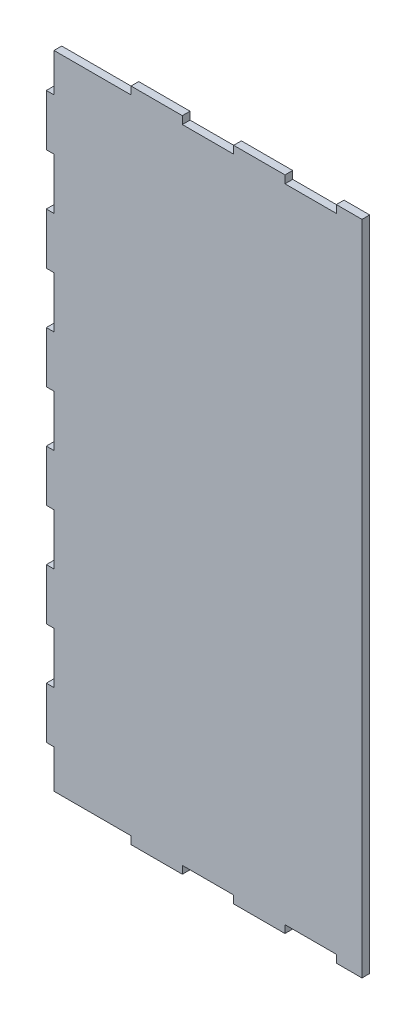
SolidWorks part; units mm, degrees
ref_plane "Front Plane" through (0, 0, 0) normal (0, 0, 1) x (1, 0, 0)
ref_plane "Top Plane" through (0, 0, 0) normal (0, 1, 0) x (1, 0, 0)
ref_plane "Right Plane" through (0, 0, 0) normal (1, 0, 0) x (0, 0, -1)
sketch "Эскиз2" plane through (0, 0, 0) normal (0, 0, 1) x (1, 0, 0)
  line L0 (252.1992, 250.1414) -> (259.9123, 250.1414)
  line L1 (259.9123, 250.1414) -> (259.9123, 254.5354)
  line L2 (259.9123, 254.5354) -> (283.6064, 254.5354)
  line L3 (283.6064, 254.5354) -> (283.6064, 250.1414)
  line L4 (283.6064, 250.1414) -> (305.7717, 250.1414)
  line L5 (305.7717, 250.1414) -> (305.7717, 254.5354)
  line L6 (305.7717, 254.5354) -> (329.4658, 254.5354)
  line L7 (329.4658, 254.5354) -> (329.4658, 250.1414)
  line L8 (329.4658, 250.1414) -> (360.0387, 250.1414)
  line L9 (360.0387, 250.1414) -> (360.0387, 226.7063)
  line L10 (360.0387, 226.7063) -> (365.7711, 226.7063)
  line L11 (365.7711, 226.7063) -> (365.7711, 208.5441)
  line L12 (365.7711, 208.5441) -> (360.0387, 208.5441)
  line L13 (360.0387, 208.5441) -> (360.0387, 191.5536)
  line L14 (360.0387, 191.5536) -> (365.7711, 191.5536)
  line L15 (365.7711, 191.5536) -> (365.7711, 173.3914)
  line L16 (365.7711, 173.3914) -> (360.0387, 173.3914)
  line L17 (360.0387, 173.3914) -> (360.0387, 156.401)
  line L18 (360.0387, 156.401) -> (365.7711, 156.401)
  line L19 (365.7711, 156.401) -> (365.7711, 138.2388)
  line L20 (365.7711, 138.2388) -> (360.0387, 138.2388)
  line L21 (360.0387, 138.2388) -> (360.0387, 121.2484)
  line L22 (360.0387, 121.2484) -> (365.7711, 121.2484)
  line L23 (365.7711, 121.2484) -> (365.7711, 103.0862)
  line L24 (365.7711, 103.0862) -> (360.0387, 103.0862)
  line L25 (360.0387, 103.0862) -> (360.0387, 86.0957)
  line L26 (360.0387, 86.0957) -> (365.7711, 86.0957)
  line L27 (365.7711, 86.0957) -> (365.7711, 67.9335)
  line L28 (365.7711, 67.9335) -> (360.0387, 67.9335)
  line L29 (360.0387, 67.9335) -> (360.0387, 50.9431)
  line L30 (360.0387, 50.9431) -> (365.7711, 50.9431)
  line L31 (365.7711, 50.9431) -> (365.7711, 32.7809)
  line L32 (365.7711, 32.7809) -> (360.0387, 32.7809)
  line L33 (360.0387, 0.0593) -> (328.8776, 0.0593)
  line L34 (328.8776, 0.0593) -> (328.8776, -4.3348)
  line L35 (328.8776, -4.3348) -> (305.1835, -4.3348)
  line L36 (305.1835, -4.3348) -> (305.1835, 0.0593)
  line L37 (305.1835, 0.0593) -> (283.0182, 0.0593)
  line L38 (283.0182, 0.0593) -> (283.0182, -4.3348)
  line L39 (283.0182, -4.3348) -> (259.3241, -4.3348)
  line L40 (259.3241, -4.3348) -> (259.3241, 0.0593)
  line L41 (259.3241, 0.0593) -> (251.611, 0.0593)
  line L42 (251.611, 0.0593) -> (237.1588, 0.0593)
  line L43 (237.1588, 0.0593) -> (237.1588, -4.3348)
  line L44 (237.1588, -4.3348) -> (213.4647, -4.3348)
  line L45 (213.4647, -4.3348) -> (213.4647, 0.0593)
  line L46 (213.4647, 0.0593) -> (191.2994, 0.0593)
  line L47 (191.2994, 0.0593) -> (191.2994, -4.3348)
  line L48 (191.2994, -4.3348) -> (167.6053, -4.3348)
  line L49 (167.6053, -4.3348) -> (167.6053, 0.0593)
  line L50 (167.6053, 0.0593) -> (145.4399, 0.0593)
  line L51 (145.4399, 0.0593) -> (145.4399, -4.3348)
  line L52 (145.4399, -4.3348) -> (121.7459, -4.3348)
  line L53 (121.7459, -4.3348) -> (121.7459, 0.0593)
  line L54 (121.7459, 0.0593) -> (99.5805, 0.0593)
  line L55 (99.5805, 0.0593) -> (99.5805, -4.3348)
  line L56 (99.5805, -4.3348) -> (75.8865, -4.3348)
  line L57 (75.8865, -4.3348) -> (75.8865, 0.0593)
  line L58 (75.8865, 0.0593) -> (53.7211, 0.0593)
  line L59 (53.7211, 0.0593) -> (53.7211, -4.3348)
  line L60 (53.7211, -4.3348) -> (30.0271, -4.3348)
  line L61 (30.0271, -4.3348) -> (30.0271, 0.0593)
  line L62 (30.0271, 0.0593) -> (0.0424, 0.0593)
  line L63 (0.0424, 0.0593) -> (0.0424, 32.7809)
  line L64 (0.0424, 32.7809) -> (-5.6901, 32.7809)
  line L65 (-5.6901, 32.7809) -> (-5.6901, 50.9431)
  line L66 (-5.6901, 50.9431) -> (0.0424, 50.9431)
  line L67 (0.0424, 50.9431) -> (0.0424, 67.9335)
  line L68 (0.0424, 67.9335) -> (-5.6901, 67.9335)
  line L69 (-5.6901, 67.9335) -> (-5.6901, 86.0957)
  line L70 (-5.6901, 86.0957) -> (0.0424, 86.0957)
  line L71 (0.0424, 86.0957) -> (0.0424, 103.0862)
  line L72 (0.0424, 103.0862) -> (-5.6901, 103.0862)
  line L73 (-5.6901, 103.0862) -> (-5.6901, 121.2484)
  line L74 (-5.6901, 121.2484) -> (0.0424, 121.2484)
  line L75 (0.0424, 121.2484) -> (0.0424, 138.2388)
  line L76 (0.0424, 138.2388) -> (-5.6901, 138.2388)
  line L77 (-5.6901, 138.2388) -> (-5.6901, 156.401)
  line L78 (-5.6901, 156.401) -> (0.0424, 156.401)
  line L79 (0.0424, 156.401) -> (0.0424, 173.3914)
  line L80 (0.0424, 173.3914) -> (-5.6901, 173.3914)
  line L81 (-5.6901, 173.3914) -> (-5.6901, 191.5536)
  line L82 (-5.6901, 191.5536) -> (0.0424, 191.5536)
  line L83 (0.0424, 191.5536) -> (0.0424, 208.5441)
  line L84 (0.0424, 208.5441) -> (-5.6901, 208.5441)
  line L85 (-5.6901, 208.5441) -> (-5.6901, 226.7063)
  line L86 (-5.6901, 226.7063) -> (0.0424, 226.7063)
  line L87 (0.0424, 226.7063) -> (0.0424, 250.1414)
  line L88 (0.0424, 250.1414) -> (30.6153, 250.1414)
  line L89 (30.6153, 250.1414) -> (30.6153, 254.5354)
  line L90 (30.6153, 254.5354) -> (54.3093, 254.5354)
  line L91 (54.3093, 254.5354) -> (54.3093, 250.1414)
  line L92 (54.3093, 250.1414) -> (76.4747, 250.1414)
  line L93 (76.4747, 250.1414) -> (76.4747, 254.5354)
  line L94 (76.4747, 254.5354) -> (100.1687, 254.5354)
  line L95 (100.1687, 254.5354) -> (100.1687, 250.1414)
  line L96 (100.1687, 250.1414) -> (122.3341, 250.1414)
  line L97 (122.3341, 250.1414) -> (122.3341, 254.5354)
  line L98 (122.3341, 254.5354) -> (146.0281, 254.5354)
  line L99 (146.0281, 254.5354) -> (146.0281, 250.1414)
  line L100 (146.0281, 250.1414) -> (168.1935, 250.1414)
  line L101 (168.1935, 250.1414) -> (168.1935, 254.5354)
  line L102 (168.1935, 254.5354) -> (191.8876, 254.5354)
  line L103 (191.8876, 254.5354) -> (191.8876, 250.1414)
  line L104 (191.8876, 250.1414) -> (214.0529, 250.1414)
  line L105 (214.0529, 250.1414) -> (214.0529, 254.5354)
  line L106 (214.0529, 254.5354) -> (237.747, 254.5354)
  line L107 (237.747, 254.5354) -> (237.747, 250.1414)
  line L108 (237.747, 250.1414) -> (252.1992, 250.1414)
  line L109 (-2.9475, -11.1911) -> (27.4972, -11.1911)
  line L110 (27.4972, -11.1911) -> (27.4972, -15.5023)
  line L111 (27.4972, -15.5023) -> (51.9003, -15.5023)
  line L112 (51.9003, -15.5023) -> (51.9003, -11.1911)
  line L113 (51.9003, -11.1911) -> (73.3564, -11.1911)
  line L114 (73.3564, -11.1911) -> (73.3564, -15.5023)
  line L115 (73.3564, -15.5023) -> (97.7419, -15.5023)
  line L116 (97.7419, -15.5023) -> (97.7419, -11.1911)
  line L117 (97.7419, -11.1911) -> (119.1409, -11.1911)
  line L118 (119.1409, -11.1911) -> (119.1409, -15.5023)
  line L119 (119.1409, -15.5023) -> (143.6357, -15.5023)
  line L120 (143.6357, -15.5023) -> (143.6357, -11.1911)
  line L121 (143.6357, -11.1911) -> (165.0694, -11.1911)
  line L122 (165.0694, -11.1911) -> (165.0694, -15.5023)
  line L123 (165.0694, -15.5023) -> (189.4359, -15.5023)
  line L124 (189.4359, -15.5023) -> (189.4359, -11.1911)
  line L125 (189.4359, -11.1911) -> (210.8089, -11.1911)
  line L126 (210.8089, -11.1911) -> (210.8089, -15.5023)
  line L127 (210.8089, -15.5023) -> (235.3017, -15.5023)
  line L128 (235.3017, -15.5023) -> (235.3017, -11.1911)
  line L129 (235.3017, -11.1911) -> (256.7496, -11.1911)
  line L130 (256.7496, -11.1911) -> (256.7496, -15.5023)
  line L131 (256.7496, -15.5023) -> (281.117, -15.5023)
  line L132 (281.117, -15.5023) -> (281.117, -11.1911)
  line L133 (281.117, -11.1911) -> (302.5894, -11.1911)
  line L134 (302.5894, -11.1911) -> (302.5894, -15.5023)
  line L135 (302.5894, -15.5023) -> (327.148, -15.5023)
  line L136 (327.148, -15.5023) -> (327.148, -11.1911)
  line L137 (327.148, -11.1911) -> (357.4727, -11.1911)
  line L138 (357.4727, -11.1911) -> (357.4727, -22.8779)
  line L139 (357.4727, -22.8779) -> (365.5155, -22.8779)
  line L140 (365.5155, -22.8779) -> (365.509, -29.7472)
  line L141 (365.509, -29.7472) -> (357.4727, -29.7472)
  line L142 (357.4727, -29.7472) -> (357.4727, -42.673)
  line L143 (357.4727, -42.673) -> (327.148, -42.673)
  line L144 (327.148, -42.673) -> (327.148, -38.9463)
  line L145 (327.148, -38.9463) -> (302.5894, -38.9463)
  line L146 (302.5894, -38.9463) -> (302.5894, -42.673)
  line L147 (302.5894, -42.673) -> (281.117, -42.673)
  line L148 (281.117, -42.673) -> (281.117, -38.9463)
  line L149 (281.117, -38.9463) -> (256.7496, -38.9463)
  line L150 (256.7496, -38.9463) -> (256.7496, -42.673)
  line L151 (256.7496, -42.673) -> (235.3017, -42.673)
  line L152 (235.3017, -42.673) -> (235.3017, -38.9463)
  line L153 (235.3017, -38.9463) -> (210.8089, -38.9463)
  line L154 (210.8089, -38.9463) -> (210.8089, -42.673)
  line L155 (210.8089, -42.673) -> (189.4359, -42.673)
  line L156 (189.4359, -42.673) -> (189.4353, -38.9463)
  line L157 (189.4353, -38.9463) -> (165.0694, -38.9463)
  line L158 (165.0694, -38.9463) -> (165.0694, -42.673)
  line L159 (165.0694, -42.673) -> (143.6357, -42.673)
  line L160 (143.6357, -42.673) -> (143.6357, -38.9463)
  line L161 (143.6357, -38.9463) -> (119.1409, -38.9463)
  line L162 (119.1409, -38.9463) -> (119.1409, -42.673)
  line L163 (119.1409, -42.673) -> (97.7419, -42.673)
  line L164 (97.7419, -42.673) -> (97.7419, -38.9463)
  line L165 (97.7419, -38.9463) -> (73.3564, -38.9463)
  line L166 (73.3564, -38.9463) -> (73.3564, -42.673)
  line L167 (73.3564, -42.673) -> (51.9003, -42.673)
  line L168 (51.9003, -42.673) -> (51.9003, -38.9463)
  line L169 (51.9003, -38.9463) -> (27.4972, -38.9463)
  line L170 (27.4972, -38.9463) -> (27.4972, -42.673)
  line L171 (27.4972, -42.673) -> (-2.9475, -42.673)
  line L172 (-2.9475, -42.673) -> (-2.9475, -29.9471)
  line L173 (-2.9475, -29.9471) -> (-9.6507, -29.9471)
  line L174 (-9.6507, -29.9471) -> (-9.6507, -23.0778)
  line L175 (-9.6507, -23.0778) -> (-2.9475, -23.0778)
  line L176 (-2.9475, -23.0778) -> (-2.9475, -11.1911)
  line L177 (60.6272, -30.2931) -> (60.6272, -23.0367)
  line L178 (60.6272, -23.0367) -> (63.4658, -23.0367)
  line L179 (63.4658, -23.0367) -> (63.4658, -30.2931)
  line L180 (63.4658, -30.2931) -> (60.6272, -30.2931)
  line L181 (30.6174, -30.2532) -> (30.6174, -23.0192)
  line L182 (30.6174, -23.0192) -> (33.456, -23.0192)
  line L183 (33.456, -23.0192) -> (33.456, -30.2532)
  line L184 (33.456, -30.2532) -> (30.6174, -30.2532)
  line L185 (90.633, -30.2432) -> (90.633, -23.0092)
  line L186 (90.633, -23.0092) -> (93.4716, -23.0092)
  line L187 (93.4716, -23.0092) -> (93.4716, -30.2432)
  line L188 (93.4716, -30.2432) -> (90.633, -30.2432)
  line L189 (120.6308, -30.2393) -> (120.6308, -23.0267)
  line L190 (120.6308, -23.0267) -> (123.4694, -23.0267)
  line L191 (123.4694, -23.0267) -> (123.4694, -30.2393)
  line L192 (123.4694, -30.2393) -> (120.6308, -30.2393)
  line L193 (180.6508, -30.1271) -> (180.6508, -23.0192)
  line L194 (180.6508, -23.0192) -> (183.4894, -23.0192)
  line L195 (183.4894, -23.0192) -> (183.4894, -30.1271)
  line L196 (183.4894, -30.1271) -> (180.6508, -30.1271)
  line L197 (153.4727, -23.0191) -> (153.4727, -27.1573)
  line L198 (153.4727, -27.1573) -> (153.4727, -30.1922)
  line L199 (153.4727, -30.1922) -> (150.6341, -30.1922)
  line L200 (150.6341, -30.1922) -> (150.6341, -23.0191)
  line L201 (150.6341, -23.0191) -> (153.4727, -23.0191)
  line L202 (210.6566, -29.9898) -> (210.6566, -23.0192)
  line L203 (210.6566, -23.0192) -> (213.4952, -23.0192)
  line L204 (213.4952, -23.0192) -> (213.4952, -29.9898)
  line L205 (213.4952, -29.9898) -> (210.6566, -29.9898)
  line L206 (244.2529, -30.006) -> (244.2529, -23.0101)
  line L207 (244.2529, -23.0101) -> (247.1018, -23.0101)
  line L208 (247.1018, -23.0101) -> (247.1018, -30.006)
  line L209 (247.1018, -30.006) -> (244.2529, -30.006)
  line L210 (402.371, 242.8158) -> (402.371, 211.9159)
  line L211 (402.371, 211.9159) -> (396.4841, 211.9159)
  line L212 (396.4841, 211.9159) -> (396.4841, 193.3537)
  line L213 (396.4841, 193.3537) -> (402.371, 193.3537)
  line L214 (402.371, 193.3537) -> (402.371, 176.7632)
  line L215 (402.371, 176.7632) -> (396.4841, 176.7632)
  line L216 (396.4841, 176.7632) -> (396.4841, 158.0098)
  line L217 (396.4841, 158.0098) -> (402.371, 158.0098)
  line L218 (402.371, 158.0098) -> (402.371, 141.6106)
  line L219 (402.371, 141.6106) -> (396.4841, 141.6106)
  line L220 (396.4841, 141.6106) -> (396.4841, 123.2484)
  line L221 (396.4841, 123.2484) -> (402.371, 123.2484)
  line L222 (402.371, 123.2484) -> (402.371, 106.458)
  line L223 (402.371, 106.458) -> (396.4841, 106.458)
  line L224 (396.4841, 106.458) -> (396.4841, 87.8958)
  line L225 (396.4841, 87.8958) -> (402.371, 87.8958)
  line L226 (402.371, 87.8958) -> (402.371, 71.3053)
  line L227 (402.371, 71.3053) -> (396.4841, 71.3053)
  line L228 (396.4841, 71.3053) -> (396.4841, 52.9431)
  line L229 (396.4841, 52.9431) -> (402.371, 52.9431)
  line L230 (402.371, 52.9431) -> (402.371, 35.9527)
  line L231 (402.371, 35.9527) -> (396.4841, 35.9527)
  line L232 (396.4841, 35.9527) -> (396.4841, 17.7905)
  line L233 (396.4841, 17.7905) -> (402.371, 17.7905)
  line L234 (402.371, 17.7905) -> (402.371, 8.4645)
  line L235 (402.371, 8.4645) -> (402.371, -22.2271)
  line L236 (402.371, -22.2271) -> (390.3312, -22.2271)
  line L237 (390.3312, -22.2271) -> (390.3312, -14.8105)
  line L238 (390.3312, -14.8105) -> (383.0324, -14.8105)
  line L239 (383.0324, -14.8105) -> (383.0324, -22.2271)
  line L240 (383.0324, -22.2271) -> (370.314, -22.2271)
  line L241 (370.314, 17.7905) -> (376.6791, 17.7905)
  line L242 (376.6791, 17.7905) -> (376.6791, 35.9527)
  line L243 (376.6791, 35.9527) -> (370.314, 35.9527)
  line L244 (370.314, 35.9527) -> (370.314, 52.9431)
  line L245 (370.314, 52.9431) -> (376.6791, 52.9431)
  line L246 (376.6791, 52.9431) -> (376.6791, 71.3053)
  line L247 (376.6791, 71.3053) -> (370.314, 71.3053)
  line L248 (370.314, 71.3053) -> (370.314, 87.8958)
  line L249 (370.314, 87.8958) -> (376.6791, 87.8958)
  line L250 (376.6791, 87.8958) -> (376.6791, 106.458)
  line L251 (376.6791, 106.458) -> (370.314, 106.458)
  line L252 (370.314, 106.458) -> (370.314, 123.2484)
  line L253 (370.314, 123.2484) -> (376.6791, 123.2484)
  line L254 (376.6791, 123.2484) -> (376.6791, 141.6106)
  line L255 (376.6791, 141.6106) -> (370.314, 141.6106)
  line L256 (370.314, 141.6106) -> (370.314, 158.0098)
  line L257 (370.314, 158.0098) -> (376.6791, 158.0098)
  line L258 (376.6791, 158.0098) -> (376.6791, 176.7632)
  line L259 (376.6791, 176.7632) -> (370.314, 176.7632)
  line L260 (370.314, 176.7632) -> (370.314, 193.3537)
  line L261 (370.314, 193.3537) -> (376.6791, 193.3537)
  line L262 (376.6791, 193.3537) -> (376.6791, 211.9159)
  line L263 (376.6791, 211.9159) -> (370.314, 211.9159)
  line L264 (370.314, 211.9159) -> (370.314, 242.8158)
  line L265 (370.314, 242.8158) -> (383.3421, 242.8158)
  line L266 (383.3421, 242.8158) -> (383.3421, 235.2429)
  line L267 (383.3421, 235.2429) -> (390.2615, 235.2429)
  line L268 (390.2615, 235.2429) -> (390.2615, 242.8158)
  line L269 (390.2615, 242.8158) -> (402.371, 242.8158)
  line L270 (382.9975, 171.629) -> (390.2539, 171.629)
  line L271 (390.2539, 171.629) -> (390.2539, 168.7904)
  line L272 (390.2539, 168.7904) -> (382.9975, 168.7904)
  line L273 (382.9975, 168.7904) -> (382.9975, 171.629)
  line L274 (383.0374, 201.6388) -> (390.2714, 201.6388)
  line L275 (390.2714, 201.6388) -> (390.2714, 198.8002)
  line L276 (390.2714, 198.8002) -> (383.0374, 198.8002)
  line L277 (383.0374, 198.8002) -> (383.0374, 201.6388)
  line L278 (383.0474, 141.6232) -> (390.2814, 141.6232)
  line L279 (390.2814, 141.6232) -> (390.2814, 138.7846)
  line L280 (390.2814, 138.7846) -> (383.0474, 138.7846)
  line L281 (383.0474, 138.7846) -> (383.0474, 141.6232)
  line L282 (383.0513, 111.6254) -> (390.2639, 111.6254)
  line L283 (390.2639, 111.6254) -> (390.2639, 108.7868)
  line L284 (390.2639, 108.7868) -> (383.0513, 108.7868)
  line L285 (383.0513, 108.7868) -> (383.0513, 111.6254)
  line L286 (383.1635, 51.6054) -> (390.2714, 51.6054)
  line L287 (390.2714, 51.6054) -> (390.2714, 48.7668)
  line L288 (390.2714, 48.7668) -> (383.1635, 48.7668)
  line L289 (383.1635, 48.7668) -> (383.1635, 51.6054)
  line L290 (390.2715, 78.7835) -> (386.1333, 78.7835)
  line L291 (386.1333, 78.7835) -> (383.0984, 78.7835)
  line L292 (383.0984, 78.7835) -> (383.0984, 81.6221)
  line L293 (383.0984, 81.6221) -> (390.2715, 81.6221)
  line L294 (390.2715, 81.6221) -> (390.2715, 78.7835)
  line L295 (383.3008, 21.5996) -> (390.2714, 21.5996)
  line L296 (390.2714, 21.5996) -> (390.2714, 18.761)
  line L297 (390.2714, 18.761) -> (383.3008, 18.761)
  line L298 (383.3008, 18.761) -> (383.3008, 21.5996)
  spline S0 degree 3 poles (360.0387, 32.7809) (360.0387, 6.279) (360.0387, 29.9698) (360.0387, 0.0593) knots 0.3 0.3 0.3 0.3 0.309091 0.309091 0.309091 0.309091
  spline S1 degree 3 poles (370.314, -22.2271) (370.314, -8.8879) (370.314, 4.4513) (370.314, 17.7905) knots 0.508197 0.508197 0.508197 0.508197 0.52459 0.52459 0.52459 0.52459
sketch "Sketch2" plane through (0, 0, 0) normal (0, 0, 1) x (1, 0, 0)
  line L0 (-2.9576, 75.0592) -> (0.0424, 75.0592)
  line L1 (0.0424, 250.0592) -> (30.0424, 250.0592)
  line L2 (0.0424, 250.0592) -> (0.0424, 235.0592)
  line L5 (-2.9576, 35.0592) -> (0.0424, 35.0592)
  line L6 (-2.9576, 35.0592) -> (-2.9576, 15.0592)
  line L7 (-2.9576, 15.0592) -> (0.0424, 15.0592)
  line L10 (-2.9576, 55.0592) -> (0.0424, 55.0592)
  line L11 (-2.9576, 75.0592) -> (-2.9576, 55.0592)
  line L12 (-2.9576, 115.0592) -> (0.0424, 115.0592)
  line L14 (-2.9576, 95.0592) -> (0.0424, 95.0592)
  line L15 (-2.9576, 115.0592) -> (-2.9576, 95.0592)
  line L16 (-2.9576, 155.0592) -> (0.0424, 155.0592)
  line L18 (-2.9576, 135.0592) -> (0.0424, 135.0592)
  line L19 (-2.9576, 155.0592) -> (-2.9576, 135.0592)
  line L20 (-2.9576, 195.0592) -> (0.0424, 195.0592)
  line L22 (-2.9576, 175.0592) -> (0.0424, 175.0592)
  line L23 (-2.9576, 195.0592) -> (-2.9576, 175.0592)
  line L24 (-2.9576, 235.0592) -> (0.0424, 235.0592)
  line L26 (-2.9576, 215.0592) -> (0.0424, 215.0592)
  line L27 (-2.9576, 235.0592) -> (-2.9576, 215.0592)
  line L28 (70.0424, 250.0592) -> (70.0424, 253.0592)
  line L30 (30.0424, 250.0592) -> (30.0424, 253.0592)
  line L31 (30.0424, 253.0592) -> (50.0424, 253.0592)
  line L32 (50.0424, 250.0592) -> (50.0424, 253.0592)
  line L34 (90.0424, 250.0592) -> (90.0424, 253.0592)
  line L35 (70.0424, 253.0592) -> (90.0424, 253.0592)
  line L36 (110.0424, 250.0592) -> (110.0424, 253.0592)
  line L39 (110.0424, 253.0592) -> (120.0424, 253.0592)
  line L119 (90.0424, 250.0592) -> (110.0424, 250.0592)
  line L120 (0.0424, 0.0592) -> (30.0424, 0.0592)
  line L125 (50.0424, 250.0592) -> (70.0424, 250.0592)
  line L130 (0.0424, 215.0592) -> (0.0424, 195.0592)
  line L132 (50.0424, 0.0592) -> (70.0424, 0.0592)
  line L133 (0.0424, 175.0592) -> (0.0424, 155.0592)
  line L135 (0.0424, 135.0592) -> (0.0424, 115.0592)
  line L137 (0.0424, 95.0592) -> (0.0424, 75.0592)
  line L138 (90.0424, 0.0592) -> (110.0424, 0.0592)
  line L139 (0.0424, 55.0592) -> (0.0424, 35.0592)
  line L140 (0.0424, 15.0592) -> (0.0424, 0.0592)
  line L156 (110.0424, -2.9408) -> (120.0424, -2.9408)
  line L158 (110.0424, 0.0592) -> (110.0424, -2.9408)
  line L159 (70.0424, -2.9408) -> (90.0424, -2.9408)
  line L160 (90.0424, 0.0592) -> (90.0424, -2.9408)
  line L161 (50.0424, 0.0592) -> (50.0424, -2.9408)
  line L162 (30.0424, -2.9408) -> (50.0424, -2.9408)
  line L163 (30.0424, 0.0592) -> (30.0424, -2.9408)
  line L164 (70.0424, 0.0592) -> (70.0424, -2.9408)
  line L190 (60.0424, 250.0592) -> (60.0424, 268.6254) construction
  line L191 (120.0424, 253.0592) -> (120.0424, -2.9408)
  line L192 (150.0424, 250.0592) -> (150.0424, 253.0592) [skipped]
  line L193 (170.0424, 250.0592) -> (170.0424, 253.0592) [skipped]
  line L194 (150.0424, 253.0592) -> (170.0424, 253.0592) [skipped]
  line L195 (190.0424, 250.0592) -> (190.0424, 253.0592) [skipped]
  line L196 (210.0424, 250.0592) -> (210.0424, 253.0592) [skipped]
  line L197 (190.0424, 253.0592) -> (210.0424, 253.0592) [skipped]
  line L198 (230.0424, 250.0592) -> (230.0424, 253.0592) [skipped]
  line L199 (250.0424, 250.0592) -> (250.0424, 253.0592) [skipped]
  line L200 (230.0424, 253.0592) -> (250.0424, 253.0592) [skipped]
  line L201 (270.0424, 250.0592) -> (270.0424, 253.0592) [skipped]
  line L202 (290.0424, 250.0592) -> (290.0424, 253.0592) [skipped]
  line L203 (270.0424, 253.0592) -> (290.0424, 253.0592) [skipped]
  line L204 (310.0424, 250.0592) -> (310.0424, 253.0592) [skipped]
  line L205 (330.0424, 250.0592) -> (330.0424, 253.0592) [skipped]
  line L206 (310.0424, 253.0592) -> (330.0424, 253.0592) [skipped]
  line L207 (130.0424, 250.0592) -> (130.0424, 253.0592) [skipped]
  point P7 (30.0424, 250.0592)
  point P14 (0.0424, 15.0592)
  point P98 (30.0424, 0.0592)
  dimension "D1" = 250
  dimension "D3" = 20
  dimension "D4" = 3
  dimension "D5" = 15
  dimension "D6" = 6
  dimension "D7" = 30
  dimension "D8" = 20
  dimension "D9" = 3
  dimension "D11" = 20
  dimension "D12" = 20
  dimension "D10" = 8
extrude "Boss-Extrude1" add sketch "Sketch2" along normal blind 3
